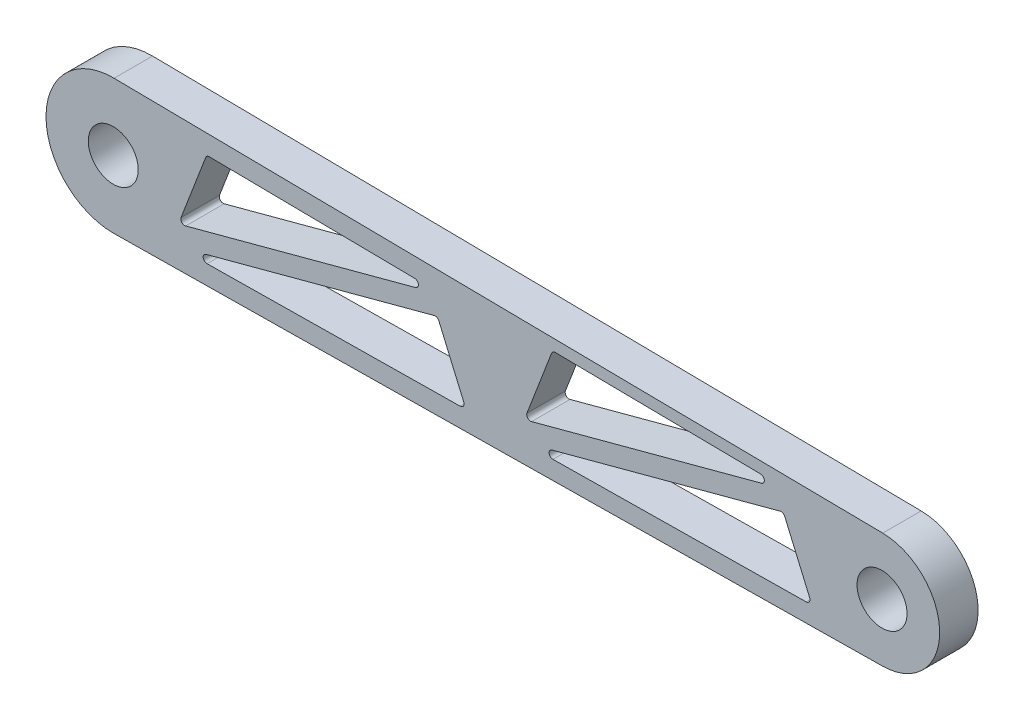
SolidWorks part; units mm, degrees
ref_plane "前视基准面" through (0, 0, 0) normal (0, 0, 1) x (1, 0, 0)
ref_plane "上视基准面" through (0, 0, 0) normal (0, 1, 0) x (1, 0, 0)
ref_plane "右视基准面" through (0, 0, 0) normal (1, 0, 0) x (0, 0, -1)
sketch "草图1" plane through (0, 0, 0) normal (0, 0, 1) x (1, 0, 0)
  line L0 (0.2188, 17.4986) -> (200.1875, 14.9988)
  line L1 (0, 0) -> (200, 0) construction
  line L2 (0.2188, -17.4986) -> (200.1875, -14.9988)
  circle A0 centre (0, 0) radius 17.5
  circle A1 centre (200, 0) radius 15
  dimension "D1" = 35
  dimension "20" = 30
  dimension "D3" = 200
extrude "凸台-拉伸1" add sketch "草图1" along normal blind 10
sketch "草图2" plane through (0, 0, 10) normal (0, 0, 1) x (1, 0, 0)
  circle A0 centre (0, 0) radius 6.5
  dimension "D1" = 13
extrude "切除-拉伸1" cut sketch "草图2" against normal blind 10
sketch "草图3" plane through (0, 0, 10) normal (0, 0, 1) x (1, 0, 0)
  line L0 (24.289, 12.1973) -> (85.6581, 11.4302)
  line L1 (85.6581, 11.4302) -> (16.9374, -6.9794)
  line L2 (16.9374, -6.9794) -> (24.289, 12.1973)
  line L3 (16.4146, -12.2958) -> (84.3461, 5.9024)
  line L4 (84.3461, 5.9024) -> (91.7811, -11.3536)
  line L5 (91.7811, -11.3536) -> (16.4146, -12.2958)
  line L6 (0.2188, -17.4986) -> (200.1875, -14.9988) construction
  line L7 (0.2188, 17.4986) -> (200.1875, 14.9988) construction
  line L8 (100.2031, 16.2487) -> (100.2031, -16.2487) construction
  line L9 (106.9328, -6.0644) -> (114.2844, 13.1124)
  line L10 (114.2844, 13.1124) -> (175.6535, 12.3452)
  line L11 (175.6535, 12.3452) -> (106.9328, -6.0644)
  line L12 (181.7765, -10.4386) -> (106.41, -11.3808)
  line L13 (106.41, -11.3808) -> (174.3414, 6.8174)
  line L14 (174.3414, 6.8174) -> (181.7765, -10.4386)
  dimension "D1" = 5
  dimension "D2" = 5
  dimension "D3" = 5
  dimension "D4" = 2
extrude "切除-拉伸2" cut sketch "草图3" against normal blind 10 contours L2 L0 L1 | L5 L3 L4 | L9 L10 L11 | L12 L13 L14
fillet "圆角1" radius 1 12 edges at (174.3414, 6.8174, 5) (181.7765, -10.4386, 5) (175.6535, 12.3452, 5) (106.41, -11.3808, 5) (106.9328, -6.0644, 5) (114.2844, 13.1124, 5) (84.3461, 5.9024, 5) (91.7811, -11.3536, 5) (16.4146, -12.2958, 5) (24.289, 12.1973, 5) (85.6581, 11.4302, 5) (16.9374, -6.9794, 5)
sketch "草图4" plane through (0, 0, 10) normal (0, 0, 1) x (1, 0, 0)
  circle A0 centre (200, 0) radius 6.5
  dimension "D1" = 13
extrude "切除-拉伸3" cut sketch "草图4" against normal blind 10
